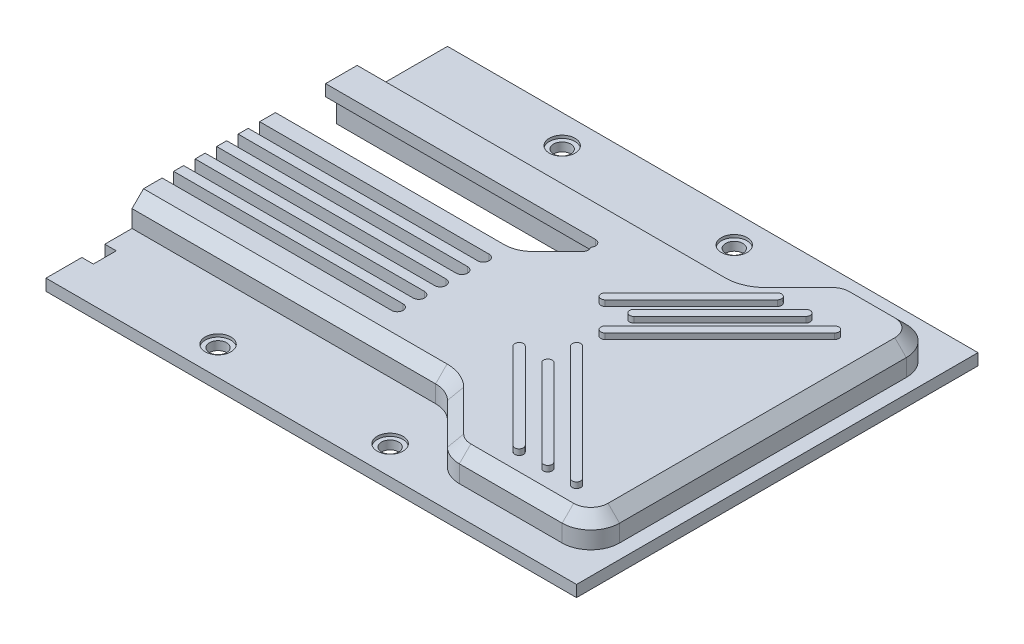
SolidWorks part; units mm, degrees
ref_plane "Front Plane" through (0, 0, 0) normal (0, 0, 1) x (1, 0, 0)
ref_plane "Top Plane" through (0, 0, 0) normal (0, 1, 0) x (1, 0, 0)
ref_plane "Right Plane" through (0, 0, 0) normal (1, 0, 0) x (0, 0, -1)
sketch "Sketch1" plane through (0, 0, 0) normal (0, 1, 0) x (1, 0, 0)
  line L1 (0, 0) -> (190, 0)
  line L2 (0, 0) -> (0, 140)
  line L3 (0, 140) -> (190, 140)
  line L4 (190, 0) -> (190, 140)
  dimension "D1" = 190
  dimension "D2" = 140
extrude "Boss-Extrude1" add sketch "Sketch1" along normal blind 4
sketch "Sketch2" plane through (0, 4, 0) normal (0, 1, 0) x (1, 0, 0)
  line L4 (135.4289, 115.4289) -> (147.0711, 127.0711)
  line L5 (154.1421, 130) -> (170, 130)
  line L6 (180, 120) -> (180, 20)
  line L12 (86.8495, 85.4289) -> (95.5064, 94.0858)
  line L13 (190, 0) -> (190, 140) construction
  line L14 (190, 140) -> (0, 140) construction
  line L15 (128.3579, 112.5) -> (0, 112.5)
  line L16 (0, 140) -> (0, 0) construction
  line L17 (94.0922, 97.5) -> (0, 97.5)
  line L18 (-80, 42.5) -> (80, 42.5) construction
  line L19 (0, 0) -> (190, 0) construction
  line L20 (170, 10) -> (134.1421, 10)
  line L21 (127.0711, 12.9289) -> (112.9289, 27.0711)
  line L22 (105.8579, 30) -> (0, 30)
  line L23 (-80, 44.5) -> (80, 44.5)
  line L29 (-80, 40.5) -> (80, 40.5)
  line L32 (-80, 50) -> (80, 50) construction
  line L35 (-80, 52) -> (80, 52)
  line L38 (-80, 48) -> (80, 48)
  line L39 (0, 82.5) -> (30.447, 82.5)
  line L40 (30.447, 82.5) -> (79.7785, 82.5)
  line L41 (-80, 57.5) -> (80, 57.5) construction
  line L42 (-80, 59.5) -> (80, 59.5)
  line L43 (-80, 55.5) -> (80, 55.5)
  line L44 (80, 65) -> (-80, 65) construction
  line L45 (80, 63) -> (-80, 63)
  line L46 (80, 67) -> (-80, 67)
  line L47 (-80, 72.5) -> (80, 72.5) construction
  line L48 (-80, 74.5) -> (80, 74.5)
  line L49 (-80, 70.5) -> (80, 70.5)
  arc A10 (170, 130) -> (180, 120) centre (170, 120) cw
  arc A11 (180, 20) -> (170, 10) centre (170, 20) cw
  arc A12 (-80, 44.5) -> (-80, 40.5) centre (-80, 42.5) ccw
  arc A13 (80, 40.5) -> (80, 44.5) centre (80, 42.5) ccw
  arc A14 (-80, 52) -> (-80, 48) centre (-80, 50) ccw
  arc A15 (80, 48) -> (80, 52) centre (80, 50) ccw
  arc A16 (-80, 59.5) -> (-80, 55.5) centre (-80, 57.5) ccw
  arc A17 (80, 55.5) -> (80, 59.5) centre (80, 57.5) ccw
  arc A18 (80, 63) -> (80, 67) centre (80, 65) ccw
  arc A19 (-80, 67) -> (-80, 63) centre (-80, 65) ccw
  arc A20 (-80, 74.5) -> (-80, 70.5) centre (-80, 72.5) ccw
  arc A21 (80, 70.5) -> (80, 74.5) centre (80, 72.5) ccw
  arc A22 (135.4289, 115.4289) -> (128.3579, 112.5) centre (128.3579, 122.5) cw
  arc A23 (147.0711, 127.0711) -> (154.1421, 130) centre (154.1421, 120) cw
  arc A24 (105.8579, 30) -> (112.9289, 27.0711) centre (105.8579, 20) cw
  arc A25 (127.0711, 12.9289) -> (134.1421, 10) centre (134.1421, 20) ccw
  arc A26 (95.5064, 94.0858) -> (94.0922, 97.5) centre (94.0922, 95.5) ccw
  arc A27 (86.8495, 85.4289) -> (79.7785, 82.5) centre (79.7785, 92.5) cw
  point P20 (0, 42.5)
  point P34 (0, 50)
  point P41 (0, 57.5)
  point P46 (0, 65)
  point P55 (180, 130)
  point P63 (0, 72.5)
  point P70 (132.5, 112.5)
  point P73 (150, 130)
  point P76 (110, 30)
  point P79 (130, 10)
  point P82 (98.9206, 97.5)
  point P85 (83.9206, 82.5)
  dimension "D1" = 10
  dimension "D4" = 10
  dimension "D25" = 2
  dimension "D26" = 2
  dimension "D27" = 2
  dimension "D41" = 2
  dimension "D42" = 10
  dimension "D38" = 2
  dimension "D43" = 2
  dimension "D44" = 10
  dimension "D45" = 10
  dimension "D2" = 10
  dimension "D3" = 10
  dimension "D5" = 50
  dimension "D6" = 30
  dimension "D7" = 135
  dimension "D8" = 132.5
  dimension "D9" = 98.9206
  dimension "D10" = 21.2132
  dimension "D11" = 15
  dimension "D12" = 15
  dimension "D13" = 135
  dimension "D14" = 17.5
  dimension "D15" = 110
  dimension "D16" = 20
  dimension "D17" = 10
  dimension "D18" = 27.5
  dimension "D19" = 30
  dimension "D28" = 160
  dimension "D29" = 160
  dimension "D30" = 160
  dimension "D31" = 42.5
  dimension "D32" = 50
  dimension "D33" = 0
  dimension "D34" = 0
  dimension "D35" = 57.5
  dimension "D36" = 65
  dimension "D37" = 72.5
  dimension "D46" = 17.5
  dimension "D47" = 20
extrude "Boss-Extrude2" add sketch "Sketch2" along normal blind 10
sketch "Sketch4" plane through (0, 0, 0) normal (0, 1, 0) x (1, 0, 0)
  line L4 (112.9289, 112.9289) -> (127.0711, 127.0711)
  line L5 (134.1421, 130) -> (150, 130)
  line L6 (160, 120) -> (160, 20)
  line L12 (86.8495, 82.9289) -> (95.5064, 91.5858)
  line L15 (105.8579, 110) -> (0, 110)
  line L17 (94.0922, 95) -> (0, 95)
  line L18 (-80, 42.5) -> (80, 42.5) construction
  line L20 (150, 10) -> (114.1421, 10)
  line L21 (107.0711, 12.9289) -> (95.4289, 24.5711)
  line L22 (88.3579, 27.5) -> (0, 27.5)
  line L23 (-80, 44.5) -> (80, 44.5)
  line L26 (-80, 35) -> (80, 35) construction
  line L27 (-80, 37) -> (80, 37)
  line L28 (-80, 33) -> (80, 33)
  line L29 (-80, 40.5) -> (80, 40.5)
  line L32 (-80, 50) -> (80, 50) construction
  line L35 (-80, 52) -> (80, 52)
  line L38 (-80, 48) -> (80, 48)
  line L39 (0, 80) -> (30.447, 80)
  line L40 (30.447, 80) -> (79.7785, 80)
  line L41 (-80, 57.5) -> (80, 57.5) construction
  line L42 (-80, 59.5) -> (80, 59.5)
  line L43 (-80, 55.5) -> (80, 55.5)
  line L44 (80, 65) -> (-80, 65) construction
  line L45 (80, 63) -> (-80, 63)
  line L46 (80, 67) -> (-80, 67)
  line L47 (-80, 72.5) -> (80, 72.5) construction
  line L48 (-80, 74.5) -> (80, 74.5)
  line L49 (-80, 70.5) -> (80, 70.5)
  arc A2 (-80, 37) -> (-80, 33) centre (-80, 35) ccw
  arc A3 (80, 33) -> (80, 37) centre (80, 35) ccw
  arc A10 (150, 130) -> (160, 120) centre (150, 120) cw
  arc A11 (160, 20) -> (150, 10) centre (150, 20) cw
  arc A12 (-80, 44.5) -> (-80, 40.5) centre (-80, 42.5) ccw
  arc A13 (80, 40.5) -> (80, 44.5) centre (80, 42.5) ccw
  arc A14 (-80, 52) -> (-80, 48) centre (-80, 50) ccw
  arc A15 (80, 48) -> (80, 52) centre (80, 50) ccw
  arc A16 (-80, 59.5) -> (-80, 55.5) centre (-80, 57.5) ccw
  arc A17 (80, 55.5) -> (80, 59.5) centre (80, 57.5) ccw
  arc A18 (80, 63) -> (80, 67) centre (80, 65) ccw
  arc A19 (-80, 67) -> (-80, 63) centre (-80, 65) ccw
  arc A20 (-80, 74.5) -> (-80, 70.5) centre (-80, 72.5) ccw
  arc A21 (80, 70.5) -> (80, 74.5) centre (80, 72.5) ccw
  arc A22 (112.9289, 112.9289) -> (105.8579, 110) centre (105.8579, 120) cw
  arc A23 (127.0711, 127.0711) -> (134.1421, 130) centre (134.1421, 120) cw
  arc A24 (88.3579, 27.5) -> (95.4289, 24.5711) centre (88.3579, 17.5) cw
  arc A25 (107.0711, 12.9289) -> (114.1421, 10) centre (114.1421, 20) ccw
  arc A26 (95.5064, 91.5858) -> (94.0922, 95) centre (94.0922, 93) ccw
  arc A27 (86.8495, 82.9289) -> (79.7785, 80) centre (79.7785, 90) cw
  point P20 (0, 42.5)
  point P27 (0, 35)
  point P34 (0, 50)
  point P41 (0, 57.5)
  point P46 (0, 65)
  point P55 (160, 130)
  point P63 (0, 72.5)
  point P70 (110, 110)
  point P73 (130, 130)
  point P76 (92.5, 27.5)
  point P79 (110, 10)
  point P82 (98.9206, 95)
  point P85 (83.9206, 80)
  dimension "D1" = 10
  dimension "D4" = 10
  dimension "D22" = 2
  dimension "D25" = 2
  dimension "D26" = 2
  dimension "D27" = 2
  dimension "D41" = 2
  dimension "D42" = 10
  dimension "D38" = 2
  dimension "D43" = 2
  dimension "D44" = 10
  dimension "D5" = 50
  dimension "D6" = 30
  dimension "D7" = 135
  dimension "D8" = 110
  dimension "D9" = 98.9206
  dimension "D10" = 21.2132
  dimension "D11" = 15
  dimension "D12" = 15
  dimension "D13" = 135
  dimension "D14" = 20
  dimension "D15" = 92.5
  dimension "D16" = 17.5
  dimension "D23" = 160
  dimension "D24" = 92.5
  dimension "D28" = 160
  dimension "D29" = 160
  dimension "D30" = 160
  dimension "D39" = 5.5
extrude "Cut-Extrude3" cut sketch "Sketch4" against normal through all both and the other way through all contours L39 L40 A27 L12 A26 L17
sketch "Sketch5" plane through (0, 0, 0) normal (0, 1, 0) x (1, 0, 0)
  line L4 (112.9289, 112.9289) -> (127.0711, 127.0711)
  line L5 (134.1421, 130) -> (150, 130)
  line L6 (160, 120) -> (160, 20)
  line L12 (86.8495, 82.9289) -> (95.5064, 91.5858)
  line L15 (105.8579, 110) -> (0, 110)
  line L17 (94.0922, 95) -> (0, 95)
  line L18 (-80, 42.5) -> (80, 42.5) construction
  line L20 (150, 10) -> (114.1421, 10)
  line L21 (107.0711, 12.9289) -> (95.4289, 24.5711)
  line L22 (88.3579, 27.5) -> (0, 27.5)
  line L23 (-80, 44.5) -> (80, 44.5)
  line L26 (-80, 35) -> (80, 35) construction
  line L27 (-80, 37) -> (80, 37)
  line L28 (-80, 33) -> (80, 33)
  line L29 (-80, 40.5) -> (80, 40.5)
  line L32 (-80, 50) -> (80, 50) construction
  line L35 (-80, 52) -> (80, 52)
  line L38 (-80, 48) -> (80, 48)
  line L39 (0, 80) -> (30.447, 80)
  line L40 (30.447, 80) -> (79.7785, 80)
  line L41 (-80, 57.5) -> (80, 57.5) construction
  line L42 (-80, 59.5) -> (80, 59.5)
  line L43 (-80, 55.5) -> (80, 55.5)
  line L44 (80, 65) -> (-80, 65) construction
  line L45 (80, 63) -> (-80, 63)
  line L46 (80, 67) -> (-80, 67)
  line L47 (-80, 72.5) -> (80, 72.5) construction
  line L48 (-80, 74.5) -> (80, 74.5)
  line L49 (-80, 70.5) -> (80, 70.5)
  arc A2 (-80, 37) -> (-80, 33) centre (-80, 35) ccw
  arc A3 (80, 33) -> (80, 37) centre (80, 35) ccw
  arc A10 (150, 130) -> (160, 120) centre (150, 120) cw
  arc A11 (160, 20) -> (150, 10) centre (150, 20) cw
  arc A12 (-80, 44.5) -> (-80, 40.5) centre (-80, 42.5) ccw
  arc A13 (80, 40.5) -> (80, 44.5) centre (80, 42.5) ccw
  arc A14 (-80, 52) -> (-80, 48) centre (-80, 50) ccw
  arc A15 (80, 48) -> (80, 52) centre (80, 50) ccw
  arc A16 (-80, 59.5) -> (-80, 55.5) centre (-80, 57.5) ccw
  arc A17 (80, 55.5) -> (80, 59.5) centre (80, 57.5) ccw
  arc A18 (80, 63) -> (80, 67) centre (80, 65) ccw
  arc A19 (-80, 67) -> (-80, 63) centre (-80, 65) ccw
  arc A20 (-80, 74.5) -> (-80, 70.5) centre (-80, 72.5) ccw
  arc A21 (80, 70.5) -> (80, 74.5) centre (80, 72.5) ccw
  arc A22 (112.9289, 112.9289) -> (105.8579, 110) centre (105.8579, 120) cw
  arc A23 (127.0711, 127.0711) -> (134.1421, 130) centre (134.1421, 120) cw
  arc A24 (88.3579, 27.5) -> (95.4289, 24.5711) centre (88.3579, 17.5) cw
  arc A25 (107.0711, 12.9289) -> (114.1421, 10) centre (114.1421, 20) ccw
  arc A26 (95.5064, 91.5858) -> (94.0922, 95) centre (94.0922, 93) ccw
  arc A27 (86.8495, 82.9289) -> (79.7785, 80) centre (79.7785, 90) cw
  point P20 (0, 42.5)
  point P27 (0, 35)
  point P34 (0, 50)
  point P41 (0, 57.5)
  point P46 (0, 65)
  point P55 (160, 130)
  point P63 (0, 72.5)
  point P70 (110, 110)
  point P73 (130, 130)
  point P76 (92.5, 27.5)
  point P79 (110, 10)
  point P82 (98.9206, 95)
  point P85 (83.9206, 80)
  dimension "D1" = 10
  dimension "D4" = 10
  dimension "D22" = 2
  dimension "D25" = 2
  dimension "D26" = 2
  dimension "D27" = 2
  dimension "D41" = 2
  dimension "D42" = 10
  dimension "D38" = 2
  dimension "D43" = 2
  dimension "D44" = 10
  dimension "D5" = 50
  dimension "D6" = 30
  dimension "D7" = 135
  dimension "D8" = 110
  dimension "D9" = 98.9206
  dimension "D10" = 21.2132
  dimension "D11" = 15
  dimension "D12" = 15
  dimension "D13" = 135
  dimension "D14" = 20
  dimension "D15" = 92.5
  dimension "D16" = 17.5
  dimension "D23" = 160
  dimension "D24" = 92.5
  dimension "D28" = 160
  dimension "D29" = 160
  dimension "D30" = 160
  dimension "D39" = 5.5
extrude "Cut-Extrude6" cut sketch "Sketch5" along normal blind 10 contours L49 A21 L48 A20 | L45 A19 L46 A18 | L43 A17 L42 A16 | L38 A15 L35 A14 | L29 A13 L23 A12 | L28 A3 L27 A2
sketch "Sketch6" plane through (0, 0, 0) normal (0, 1, 0) x (1, 0, 0)
  line L4 (112.9289, 112.9289) -> (127.0711, 127.0711)
  line L5 (134.1421, 130) -> (150, 130)
  line L6 (160, 120) -> (160, 20)
  line L12 (86.8495, 82.9289) -> (95.5064, 91.5858)
  line L15 (105.8579, 110) -> (0, 110)
  line L17 (94.0922, 95) -> (0, 95)
  line L18 (-80, 42.5) -> (80, 42.5) construction
  line L20 (150, 10) -> (114.1421, 10)
  line L21 (107.0711, 12.9289) -> (95.4289, 24.5711)
  line L22 (88.3579, 27.5) -> (0, 27.5)
  line L23 (-80, 44.5) -> (80, 44.5)
  line L26 (-80, 35) -> (80, 35) construction
  line L27 (-80, 37) -> (80, 37)
  line L28 (-80, 33) -> (80, 33)
  line L29 (-80, 40.5) -> (80, 40.5)
  line L32 (-80, 50) -> (80, 50) construction
  line L35 (-80, 52) -> (80, 52)
  line L38 (-80, 48) -> (80, 48)
  line L39 (0, 80) -> (30.447, 80)
  line L40 (30.447, 80) -> (79.7785, 80)
  line L41 (-80, 57.5) -> (80, 57.5) construction
  line L42 (-80, 59.5) -> (80, 59.5)
  line L43 (-80, 55.5) -> (80, 55.5)
  line L44 (80, 65) -> (-80, 65) construction
  line L45 (80, 63) -> (-80, 63)
  line L46 (80, 67) -> (-80, 67)
  line L47 (-80, 72.5) -> (80, 72.5) construction
  line L48 (-80, 74.5) -> (80, 74.5)
  line L49 (-80, 70.5) -> (80, 70.5)
  line L51 (100, 101.2589) -> (0, 101.2589)
  line L52 (100, 101.2589) -> (100, 30.6589)
  line L53 (100, 30.6589) -> (0, 30.6589)
  line L54 (0, 101.2589) -> (0, 30.6589)
  arc A2 (-80, 37) -> (-80, 33) centre (-80, 35) ccw
  arc A3 (80, 33) -> (80, 37) centre (80, 35) ccw
  arc A10 (150, 130) -> (160, 120) centre (150, 120) cw
  arc A11 (160, 20) -> (150, 10) centre (150, 20) cw
  arc A12 (-80, 44.5) -> (-80, 40.5) centre (-80, 42.5) ccw
  arc A13 (80, 40.5) -> (80, 44.5) centre (80, 42.5) ccw
  arc A14 (-80, 52) -> (-80, 48) centre (-80, 50) ccw
  arc A15 (80, 48) -> (80, 52) centre (80, 50) ccw
  arc A16 (-80, 59.5) -> (-80, 55.5) centre (-80, 57.5) ccw
  arc A17 (80, 55.5) -> (80, 59.5) centre (80, 57.5) ccw
  arc A18 (80, 63) -> (80, 67) centre (80, 65) ccw
  arc A19 (-80, 67) -> (-80, 63) centre (-80, 65) ccw
  arc A20 (-80, 74.5) -> (-80, 70.5) centre (-80, 72.5) ccw
  arc A21 (80, 70.5) -> (80, 74.5) centre (80, 72.5) ccw
  arc A22 (112.9289, 112.9289) -> (105.8579, 110) centre (105.8579, 120) cw
  arc A23 (127.0711, 127.0711) -> (134.1421, 130) centre (134.1421, 120) cw
  arc A24 (88.3579, 27.5) -> (95.4289, 24.5711) centre (88.3579, 17.5) cw
  arc A25 (107.0711, 12.9289) -> (114.1421, 10) centre (114.1421, 20) ccw
  arc A26 (95.5064, 91.5858) -> (94.0922, 95) centre (94.0922, 93) ccw
  arc A27 (86.8495, 82.9289) -> (79.7785, 80) centre (79.7785, 90) cw
  point P20 (0, 42.5)
  point P27 (0, 35)
  point P34 (0, 50)
  point P41 (0, 57.5)
  point P46 (0, 65)
  point P55 (160, 130)
  point P63 (0, 72.5)
  point P70 (110, 110)
  point P73 (130, 130)
  point P76 (92.5, 27.5)
  point P79 (110, 10)
  point P82 (98.9206, 95)
  point P85 (83.9206, 80)
  dimension "D1" = 10
  dimension "D4" = 10
  dimension "D22" = 2
  dimension "D25" = 2
  dimension "D26" = 2
  dimension "D27" = 2
  dimension "D41" = 2
  dimension "D42" = 10
  dimension "D38" = 2
  dimension "D43" = 2
  dimension "D44" = 10
  dimension "D5" = 50
  dimension "D6" = 30
  dimension "D7" = 135
  dimension "D8" = 110
  dimension "D9" = 98.9206
  dimension "D10" = 21.2132
  dimension "D11" = 15
  dimension "D12" = 15
  dimension "D13" = 135
  dimension "D14" = 20
  dimension "D15" = 92.5
  dimension "D16" = 17.5
  dimension "D17" = 70.6
  dimension "D18" = 100
  dimension "D19" = 100
  dimension "D23" = 160
  dimension "D24" = 92.5
  dimension "D28" = 160
  dimension "D29" = 160
  dimension "D30" = 160
  dimension "D39" = 5.5
extrude "Cut-Extrude8" cut sketch "Sketch6" along normal blind 10 contours L52 L53 L54 L51
sketch "Sketch7" plane through (0, 4, 0) normal (0, 1, 0) x (1, 0, 0)
  line L0 (0, 0) -> (190, 0) construction
  line L1 (190, 140) -> (185, 140)
  line L2 (190, 140) -> (190, 0)
  line L3 (190, 0) -> (185, 0)
  line L4 (185, 140) -> (185, 0)
  dimension "D1" = 5
extrude "Cut-Extrude9" cut sketch "Sketch7" against normal blind 10
sketch "Sketch9" plane through (0, 14, 0) normal (0, 1, 0) x (1, 0, 0)
  line L0 (145, 20) -> (115, 50) construction
  line L3 (155, 20) -> (125, 50) construction
  line L4 (153.9393, 18.9393) -> (123.9393, 48.9393)
  line L5 (156.0607, 21.0607) -> (126.0607, 51.0607)
  line L6 (82, 65) -> (196.1975, 65) construction
  line L7 (125, 60) -> (165, 20) construction
  line L8 (126.0607, 61.0607) -> (166.0607, 21.0607)
  line L9 (123.9393, 58.9393) -> (163.9393, 18.9393)
  line L10 (185, 140) -> (185, 0) construction
  line L11 (0, 0) -> (185, 0) construction
  line L12 (170, 10) -> (134.1421, 10) construction
  line L13 (143.9393, 18.9393) -> (113.9393, 48.9393)
  line L14 (146.0607, 21.0607) -> (116.0607, 51.0607)
  line L15 (145, 110) -> (115, 80) construction
  line L17 (143.9393, 111.0607) -> (113.9393, 81.0607)
  line L18 (146.0607, 108.9393) -> (116.0607, 78.9393)
  line L19 (155, 110) -> (125, 80) construction
  line L20 (153.9393, 111.0607) -> (123.9393, 81.0607)
  line L21 (156.0607, 108.9393) -> (126.0607, 78.9393)
  line L22 (125, 70) -> (165, 110) construction
  line L23 (126.0607, 68.9393) -> (166.0607, 108.9393)
  line L24 (123.9393, 71.0607) -> (163.9393, 111.0607)
  arc A2 (153.9393, 18.9393) -> (156.0607, 21.0607) centre (155, 20) ccw
  arc A3 (126.0607, 51.0607) -> (123.9393, 48.9393) centre (125, 50) ccw
  arc A4 (126.0607, 61.0607) -> (123.9393, 58.9393) centre (125, 60) ccw
  arc A5 (163.9393, 18.9393) -> (166.0607, 21.0607) centre (165, 20) ccw
  arc A6 (143.9393, 18.9393) -> (146.0607, 21.0607) centre (145, 20) ccw
  arc A7 (116.0607, 51.0607) -> (113.9393, 48.9393) centre (115, 50) ccw
  arc A9 (80, 63) -> (80, 67) centre (80, 65) ccw construction
  arc A10 (143.9393, 111.0607) -> (146.0607, 108.9393) centre (145, 110) cw
  arc A11 (116.0607, 78.9393) -> (113.9393, 81.0607) centre (115, 80) cw
  arc A12 (153.9393, 111.0607) -> (156.0607, 108.9393) centre (155, 110) cw
  arc A13 (126.0607, 78.9393) -> (123.9393, 81.0607) centre (125, 80) cw
  arc A14 (126.0607, 68.9393) -> (123.9393, 71.0607) centre (125, 70) cw
  arc A15 (163.9393, 111.0607) -> (166.0607, 108.9393) centre (165, 110) cw
  point P3 (130, 35)
  point P8 (140, 35)
  point P19 (145, 40)
  point P34 (130, 95)
  point P42 (140, 95)
  point P49 (145, 90)
  dimension "D11" = 40
  dimension "D12" = 45
  dimension "D13" = 60
  dimension "D7" = 1.5
  dimension "D8" = 1.5
  dimension "D9" = 1.5
  dimension "D1" = 20
  dimension "D2" = 20
  dimension "D3" = 45
  dimension "D4" = 30
  dimension "D5" = 20
  dimension "D6" = 45
  dimension "D10" = 20
  dimension "D14" = 50
  dimension "D15" = 50
extrude "Boss-Extrude3" add sketch "Sketch9" along normal blind 2
sketch "Sketch10" plane through (0, 4, 0) normal (0, 1, 0) x (1, 0, 0)
  line L0 (0, 30) -> (0, 0) construction
  line L1 (0, 20.5) -> (4, 20.5)
  line L2 (0, 20.5) -> (0, 12.5)
  line L3 (0, 12.5) -> (4, 12.5)
  line L4 (4, 20.5) -> (4, 12.5)
  line L5 (105.8579, 30) -> (0, 30) construction
  dimension "D1" = 9.5
  dimension "D2" = 8
  dimension "D3" = 4
extrude "Cut-Extrude11" cut sketch "Sketch10" against normal blind 10
sketch "Sketch11" plane through (0, 4, 0) normal (0, 1, 0) x (1, 0, 0)
  line L0 (185, 70) -> (-17.7411, 70) construction
  line L1 (185, 140) -> (185, 0) construction
  line L2 (0, 0) -> (185, 0) construction
  circle A0 centre (50, 10) radius 3
  circle A1 centre (110, 10) radius 3
  circle A2 centre (50, 130) radius 3
  circle A3 centre (110, 130) radius 3
  dimension "D1" = 6
  dimension "D2" = 6
  dimension "D4" = 135
  dimension "D5" = 75
  dimension "D6" = 10
  dimension "D3" = 10
extrude "Cut-Extrude12" cut sketch "Sketch11" against normal blind 10
sketch "Sketch13" plane through (0, 4, 0) normal (0, 1, 0) x (1, 0, 0)
  line L0 (165, 70) -> (-17.7411, 70) construction
  line L1 (185, 140) -> (185, 0) construction
  circle A0 centre (50, 10) radius 4.5
  circle A1 centre (110, 10) radius 4.5
  circle A2 centre (50, 130) radius 4.5
  circle A3 centre (110, 130) radius 4.5
  dimension "D1" = 9
  dimension "D2" = 9
  dimension "D4" = 135
  dimension "D3" = 75
extrude "Cut-Extrude16" cut sketch "Sketch13" against normal blind 1
chamfer "Chamfer1" distance 4 distance2 4 13 edges at (52.9289, 14, -30) (109.6847, 14, -29.2388) (120, 14, -20) (130.3153, 14, -10.7612) (152.0711, 14, -10) (177.0711, 14, -12.9289) (180, 14, -70) (177.0711, 14, -127.0711) (162.0711, 14, -130) (150.3153, 14, -129.2388) (141.25, 14, -121.25) (132.1847, 14, -113.2612) (64.1789, 14, -112.5)
